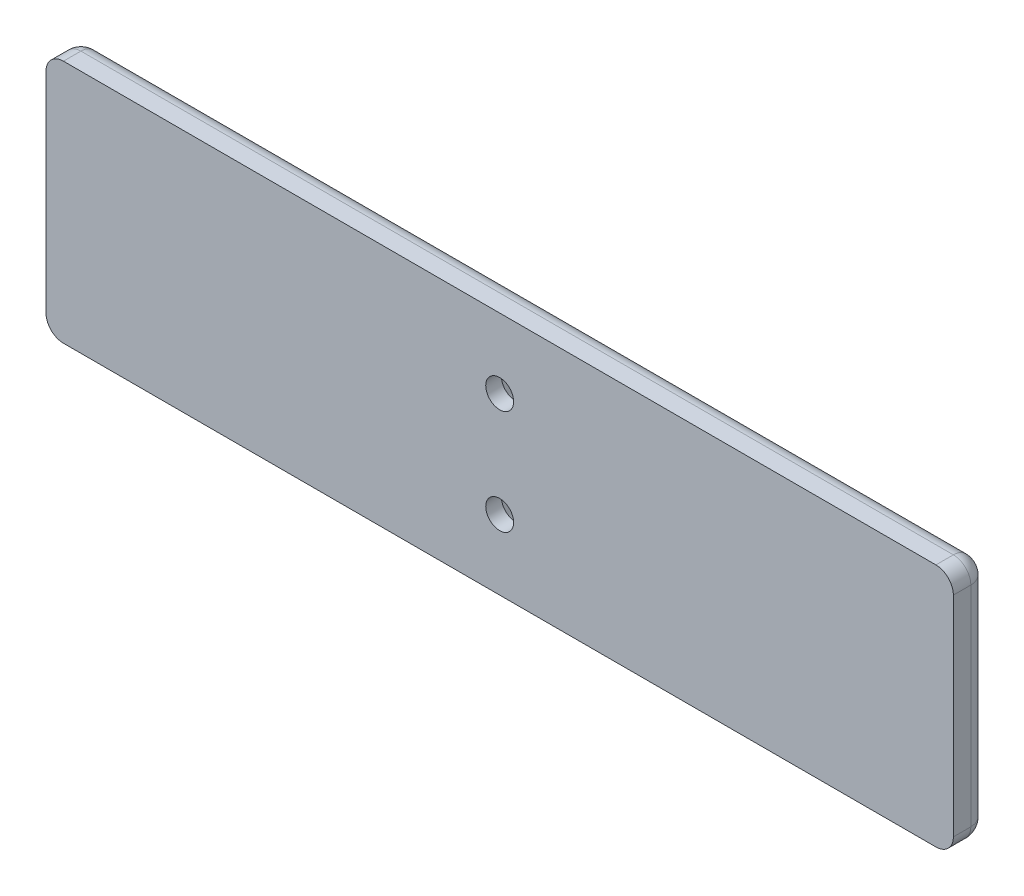
SolidWorks part; units mm, degrees
ref_plane "Front Plane" through (0, 0, 0) normal (0, 0, 1) x (1, 0, 0)
ref_plane "Top Plane" through (0, 0, 0) normal (0, 1, 0) x (1, 0, 0)
ref_plane "Right Plane" through (0, 0, 0) normal (1, 0, 0) x (0, 0, -1)
sketch "草图1" plane through (0, 0, 0) normal (0, 0, 1) x (1, 0, 0)
  line L1 (52, 14) -> (0, 14)
  line L2 (52, 14) -> (52, 0)
  line L3 (52, 0) -> (0, 0)
  line L4 (0, 14) -> (0, 0)
extrude "凸台-拉伸1" add sketch "草图1" along normal blind 2
ref_plane "基准面1" through (26, 0, 0) normal (1, 0, 0) x (0, 0, -1)
sketch "草图5" plane through (26, 0, 0) normal (1, 0, 0) x (0, 0, -1)
  line L0 (0, 4) -> (0, 2.6)
  line L1 (0, 2.6) -> (-1.1, 3.2)
  line L2 (-1.1, 3.2) -> (-2, 3.2)
  line L3 (0, 4) -> (-2, 4)
  line L4 (-2, 0) -> (-2, 14) construction
  line L5 (-2, 4) -> (-2, 3.2)
sketch "草图6" plane through (26, 0, 0) normal (1, 0, 0) x (0, 0, -1)
  line L0 (0, 10) -> (0, 11.4)
  line L1 (0, 11.4) -> (-1.1, 10.8)
  line L2 (-1.1, 10.8) -> (-2, 10.8)
  line L3 (0, 10) -> (-2, 10)
  line L4 (-2, 10) -> (-2, 10.8)
fillet "圆角2" radius 1 8 edges at (0, 0, 1) (0, 14, 1) (52, 14, 1) (52, 0, 1) (0, 7, 0) (26, 0, 0) (52, 7, 0) (26, 14, 0)
revolve "切除-旋转4" cut sketch "草图6" angle 360 about L3
revolve "切除-旋转5" cut sketch "草图5" angle 360 about L3
